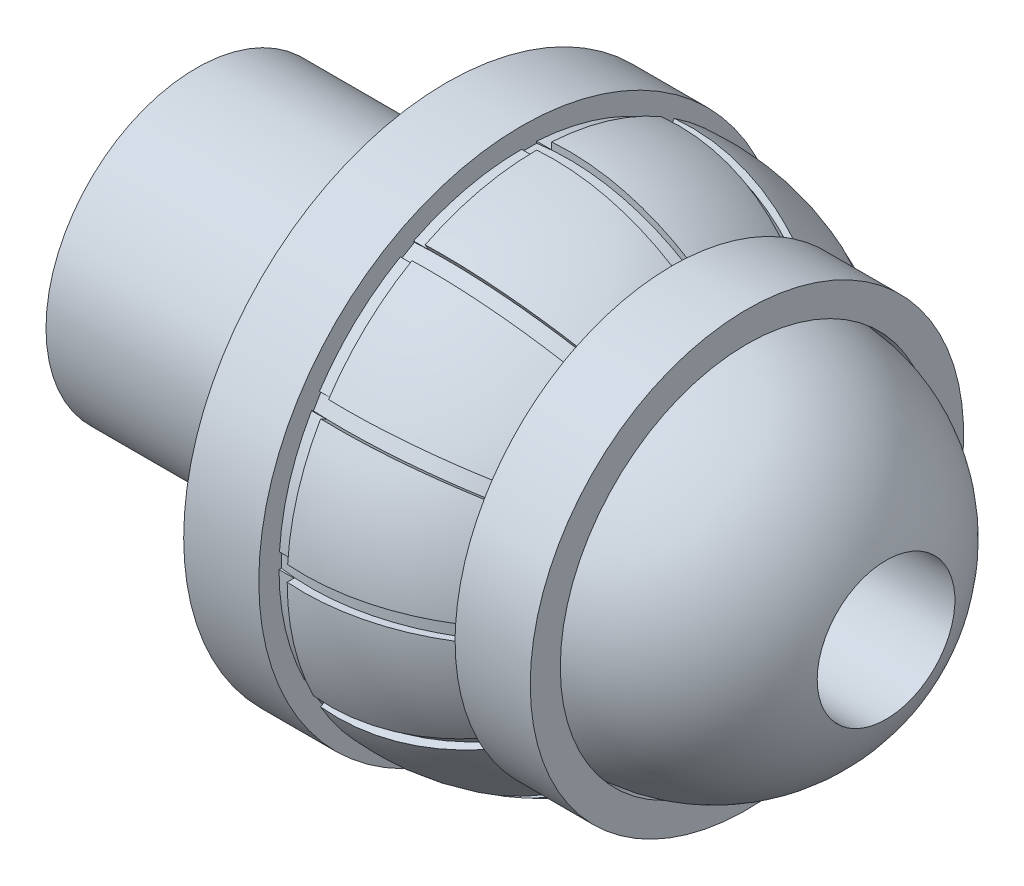
SolidWorks part; units mm, degrees
ref_plane "Plan de face" through (0, 0, 0) normal (0, 0, 1) x (1, 0, 0)
ref_plane "Plan de dessus" through (0, 0, 0) normal (0, 1, 0) x (1, 0, 0)
ref_plane "Plan de droite" through (0, 0, 0) normal (1, 0, 0) x (0, 0, -1)
sketch "Esquisse3" plane through (0, 0, 0) normal (0, 0, 1) x (1, 0, 0)
  line L0 (5, 17.5) -> (5, 16.5)
  line L1 (0, 17.5) -> (5, 17.5)
  line L2 (-14.7627, 0) -> (0, 0) construction
  line L3 (20, 14.4267) -> (15, 14.4267)
  line L5 (18, 12.4267) -> (20, 12.4267)
  line L8 (0, 17.5) -> (0, 0)
  line L9 (0, 0) -> (30, 0)
  line L13 (20, 12.4267) -> (20, 14.4267)
  arc A0 (5, 16.5) -> (15, 14.4267) centre (7.1366, 1.653) cw
  arc A1 (18, 12.4267) -> (30, 0) centre (18, 0.4193) cw
  dimension "D3" = 15
  dimension "D11" = 1
  dimension "D2" = 10
  dimension "D5" = 10
  dimension "D7" = 2
  dimension "D8" = 2
  dimension "D9" = 5
  dimension "D10" = 5
  dimension "D12" = 17.5
revolve "Révolution3" add sketch "Esquisse3" angle 360 about L2
ref_plane "Plan1" through (0, 17.5, 0) normal (0, 1, 0) x (1, 0, 0)
sketch "Esquisse8" plane through (0, 0, 0) normal (0, 1, 0) x (1, 0, 0)
  line L0 (5, 16.5) -> (5, 16)
  line L1 (5, -17.5) -> (5, 17.5) construction
  line L2 (15, 14.4267) -> (15, 13.9267)
  arc A0 (5, 16.5) -> (15, 14.4267) centre (7.1366, 1.653) cw
  arc A1 (5, 16) -> (15, 13.9267) centre (7.1366, 1.153) cw
  arc A2 (15, 14.4267) -> (5, 16.5) centre (7.1366, 1.653) ccw construction
  dimension "D2" = 15
  dimension "D1" = 0.5
extrude "Enlèv. mat.-Extru.2" cut sketch "Esquisse8" against normal blind 1
pattern_circular "Répétition circulaire1" count 12 every 30 about axis through (0, 0, 0) along (1, 0, 0) of "Enlèv. mat.-Extru.2"
sketch "Esquisse9" plane through (5, 0, 0) normal (1, 0, 0) x (0, 0, -1)
  circle A0 centre (0, 0) radius 16.653
  circle A1 centre (0, 0) radius 16.153
  dimension "D1" = 33.3059
  dimension "D2" = 0.5
extrude "Enlèv. mat.-Extru.3" cut sketch "Esquisse9" along normal blind 1
scale "Echelle3" scale about origin uniform scaling yes scale factor 0.6
sketch "Esquisse12" plane through (0, 0, 0) normal (-1, 0, 0) x (0, 0, 1)
  circle A0 centre (0, 0) radius 6
  dimension "D1" = 12
extrude "Boss.-Extru.2" add sketch "Esquisse12" along normal blind 10
sketch "Esquisse13" plane through (-10, 0, 0) normal (-1, 0, 0) x (0, 0, 1)
  circle A0 centre (0, 0) radius 2.75
  dimension "D1" = 5.5
extrude "Enlèv. mat.-Extru.5" cut sketch "Esquisse13" against normal through all
